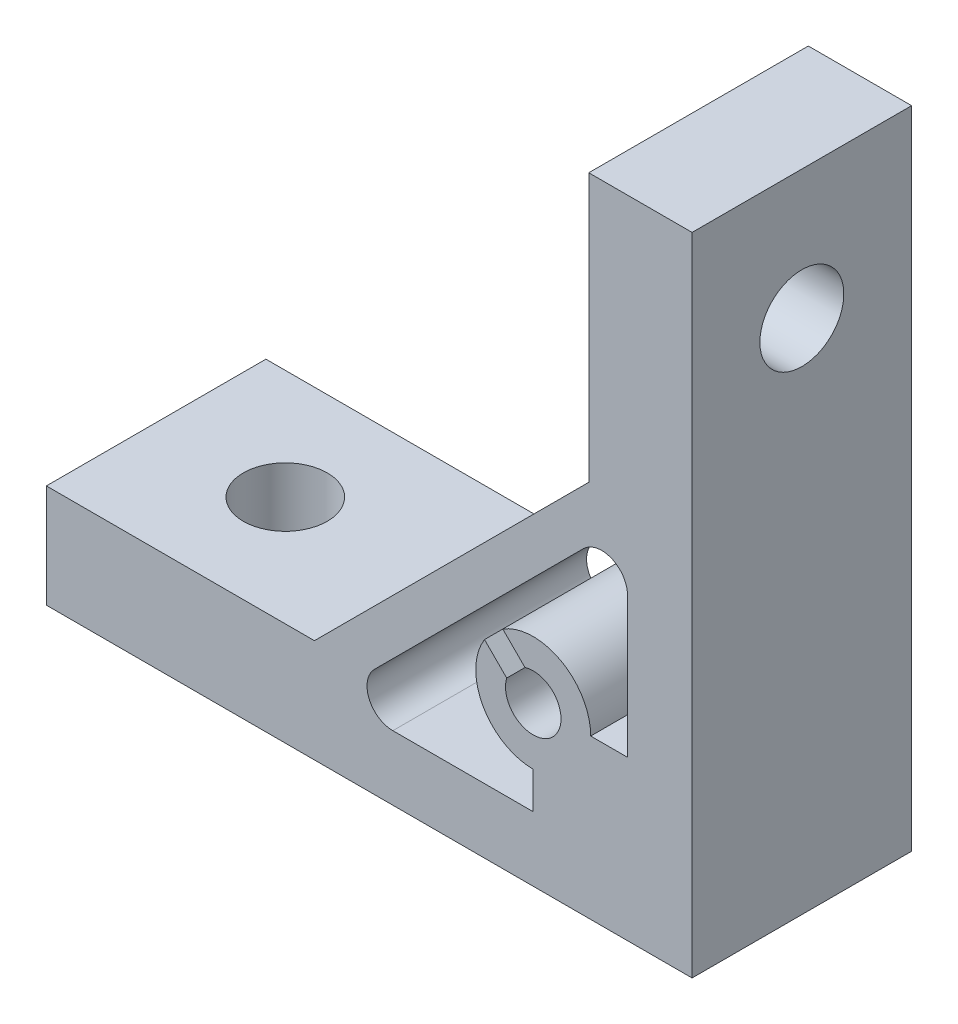
SolidWorks part; units mm, degrees
ref_plane "前视基准面" through (0, 0, 0) normal (0, 0, 1) x (1, 0, 0)
ref_plane "上视基准面" through (0, 0, 0) normal (0, 1, 0) x (1, 0, 0)
ref_plane "右视基准面" through (0, 0, 0) normal (1, 0, 0) x (0, 0, -1)
sketch "草图1" plane through (0, 0, 0) normal (0, 0, 1) x (1, 0, 0)
  line B0 (0, 0) -> (50, 0)
  line B1 (50, 0) -> (50, 50)
  line B2 (0, 8) -> (20.7574, 8)
  line B3 (42, 29.2426) -> (42, 50)
  line B4 (0, 8) -> (0, 0)
  line B5 (42, 50) -> (50, 50)
  line B6 (37.0613, 14.3529) -> (35.341, 16.0733)
  line B7 (35.6471, 12.9387) -> (33.9267, 14.659)
  line B8 (25.4142, 8.4142) -> (41.5858, 24.5858)
  line B9 (20.7574, 8) -> (42, 29.2426)
  line B10 (26.8284, 5) -> (37.7, 5)
  line B11 (45, 23.1716) -> (45, 12.3)
  line B12 (37.7, 5) -> (37.7, 7.85)
  line B13 (42.15, 12.3) -> (45, 12.3)
  arc B14 (33.9267, 14.659) -> (37.7, 7.85) centre (37.7, 12.3) ccw
  arc B15 (42.15, 12.3) -> (35.341, 16.0733) centre (37.7, 12.3) ccw
  arc B16 (35.6471, 12.9387) -> (37.0613, 14.3529) centre (37.7, 12.3) ccw
  arc B17 (25.4142, 8.4142) -> (26.8284, 5) centre (26.8284, 7) ccw
  arc B18 (45, 23.1716) -> (41.5858, 24.5858) centre (43, 23.1716) ccw
sketch_block_instance "A$C19004297-1"
sketch_block "A$C19004297"
extrude "凸台-拉伸1" add sketch "草图1" along normal mid plane 17
sketch "草图3" plane through (0, 8, 0) normal (0, 1, 0) x (1, 0, 0)
  line L0 (0, -8.5) -> (0, 8.5) construction
  circle A0 centre (10, 0) radius 3.25
  dimension "D1" = 10
extrude "切除-拉伸1" cut sketch "草图3" against normal blind 17
sketch "草图4" plane through (6.3787, -6.3787, 0) normal (-0.7071, 0.7071, 0) x (0, 0, 1)
  line L0 (8.5, 35.3553) -> (-8.5, 35.3553) construction
  line L1 (8.5, 50.3762) -> (8.5, 20.3345) construction
  line L2 (-8.5, 50.3762) -> (-8.5, 20.3345) construction
ref_plane "基准面2" through (25, 25, 0) normal (-0.7071, -0.7071, 0) x (0, 0, 1)
mirror "镜向1" about plane through (25, 25, 0) normal (-0.7071, -0.7071, 0) of "切除-拉伸1"
